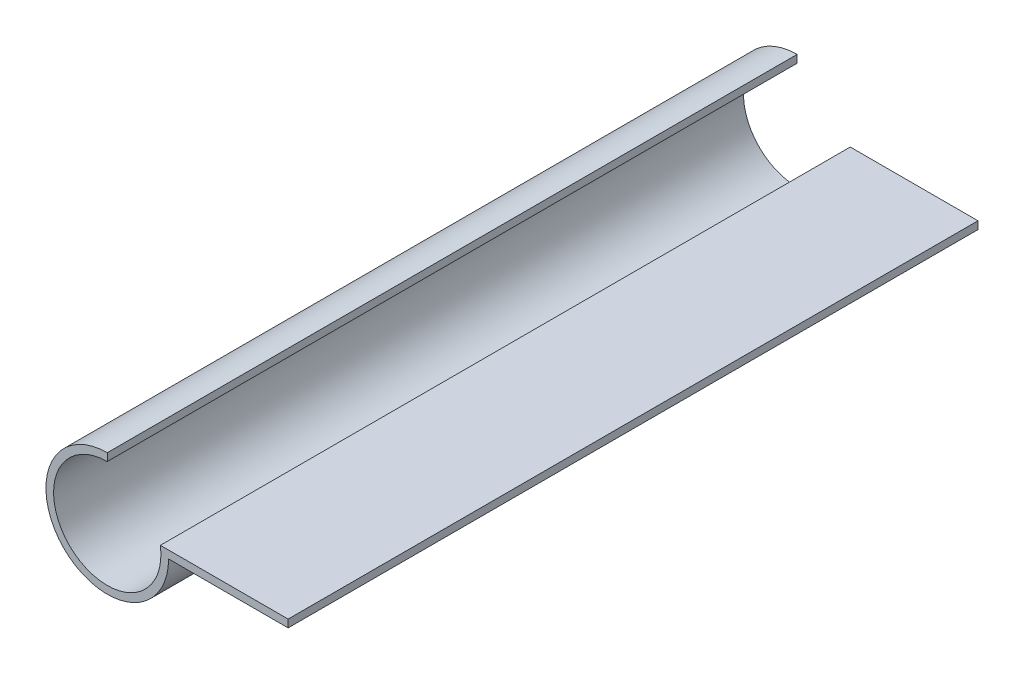
SolidWorks part; units mm, degrees
ref_plane "Front Plane" through (0, 0, 0) normal (0, 0, 1) x (1, 0, 0)
ref_plane "Top Plane" through (0, 0, 0) normal (0, 1, 0) x (1, 0, 0)
ref_plane "Right Plane" through (0, 0, 0) normal (1, 0, 0) x (0, 0, -1)
sketch "Sketch1" plane through (0, 0, 0) normal (0, 0, 1) x (1, 0, 0)
  line L0 (7.0785, 0) -> (2.4, 0)
  line L1 (7.0785, 0) -> (7.0785, 0.3)
  line L2 (7.0785, 0.3) -> (2.0785, 0.3)
  line L3 (0, 2.1) -> (0, 2.4)
  arc A0 (0, 2.1) -> (2.0785, 0.3) centre (0, 0) ccw
  arc A1 (0, 2.4) -> (2.4, 0) centre (0, 0) ccw
  circle A2 centre (0, 0) radius 2.4 construction
  circle A3 centre (0, 0) radius 2.1 construction
  dimension "D1" = 4.2
  dimension "D3" = 5
  dimension "D4" = 0.3
  dimension "D2" = 0.3
extrude "Boss-Extrude1" add sketch "Sketch1" along normal blind 27 contours A0 L2 L1 L0 A1 L3
equation "\"motorDia\"= 4.2mm"
equation "\"Width\" = 27mm"
equation "\"D1@Sketch1\"=\"motorDia\""
equation "\"D1@Boss-Extrude1\"=\"Width\""
